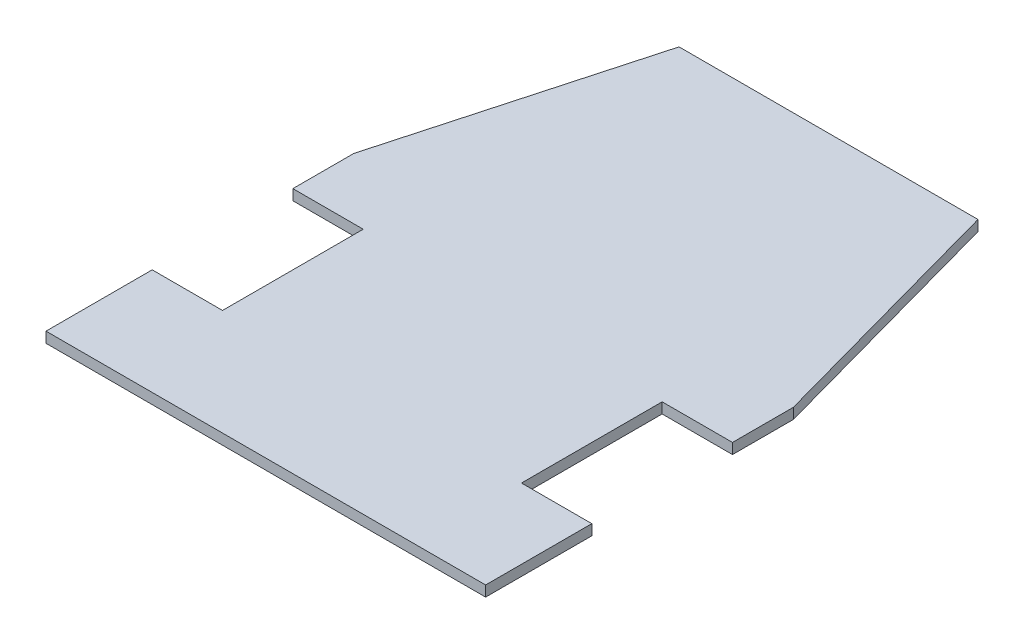
SolidWorks part; units mm, degrees
ref_plane "Front Plane" through (0, 0, 0) normal (0, 0, 1) x (1, 0, 0)
ref_plane "Top Plane" through (0, 0, 0) normal (0, 1, 0) x (1, 0, 0)
ref_plane "Right Plane" through (0, 0, 0) normal (1, 0, 0) x (0, 0, -1)
sketch "Sketch1" plane through (0, 0, 0) normal (0, 1, 0) x (1, 0, 0)
  line L0 (0, 0) -> (0, 60.3889)
  line L1 (0, 0) -> (250, 0)
  line L3 (40, 320) -> (210, 320)
  line L4 (250, 0) -> (250, 60.3889)
  line L5 (0, 60.3889) -> (40, 60.3889)
  line L7 (250, 175) -> (210, 320)
  line L8 (0, 175) -> (40, 320)
  line L9 (40, 60.3889) -> (40, 140.3889)
  line L10 (40, 140.3889) -> (0, 140.3889)
  line L11 (250, 140.3889) -> (250, 175)
  line L12 (250, 60.3889) -> (210, 60.3889)
  line L14 (250, 140.3889) -> (210, 140.3889)
  line L15 (210, 60.3889) -> (210, 140.3889)
  line L17 (0, 140.3889) -> (0, 175)
  dimension "D1" = 250
  dimension "D2" = 320
  dimension "D3" = 175
  dimension "D4" = 170
  dimension "D5" = 175
  dimension "D6" = 40
extrude "Boss-Extrude1" add sketch "Sketch1" along normal blind 6
